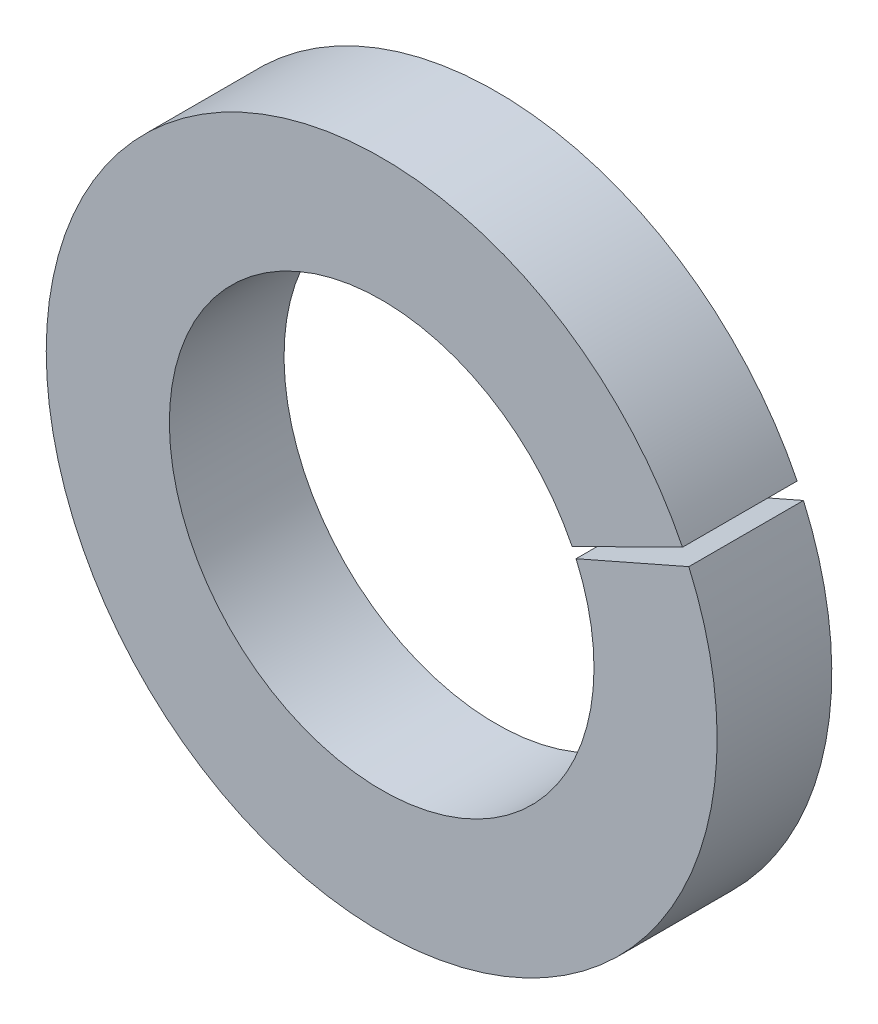
SolidWorks part; units mm, degrees
ref_plane "前视基准面" through (0, 0, 0) normal (0, 0, 1) x (1, 0, 0)
ref_plane "上视基准面" through (0, 0, 0) normal (0, 1, 0) x (1, 0, 0)
ref_plane "右视基准面" through (0, 0, 0) normal (1, 0, 0) x (0, 0, -1)
sketch "草图1" plane through (0, 0, 0) normal (0, 0, 1) x (1, 0, 0)
  circle A0 centre (0, 0) radius 7.9
  circle A1 centre (0, 0) radius 5
  dimension "D1" = 10
  dimension "D2" = 15.8
extrude "凸台-拉伸1" add sketch "草图1" along normal blind 2.7
sketch "草图2" plane through (0, 0, 2.7) normal (0, 0, 1) x (1, 0, 0)
  line L0 (0, 0) -> (8.1715, 4.0337)
  line L1 (8.1715, 4.0337) -> (8.1715, 3.5879)
  line L2 (8.1715, 3.5879) -> (0, 0)
  point P3 (8.1715, 3.5879)
extrude "切除-拉伸1" cut sketch "草图2" against normal blind 10
